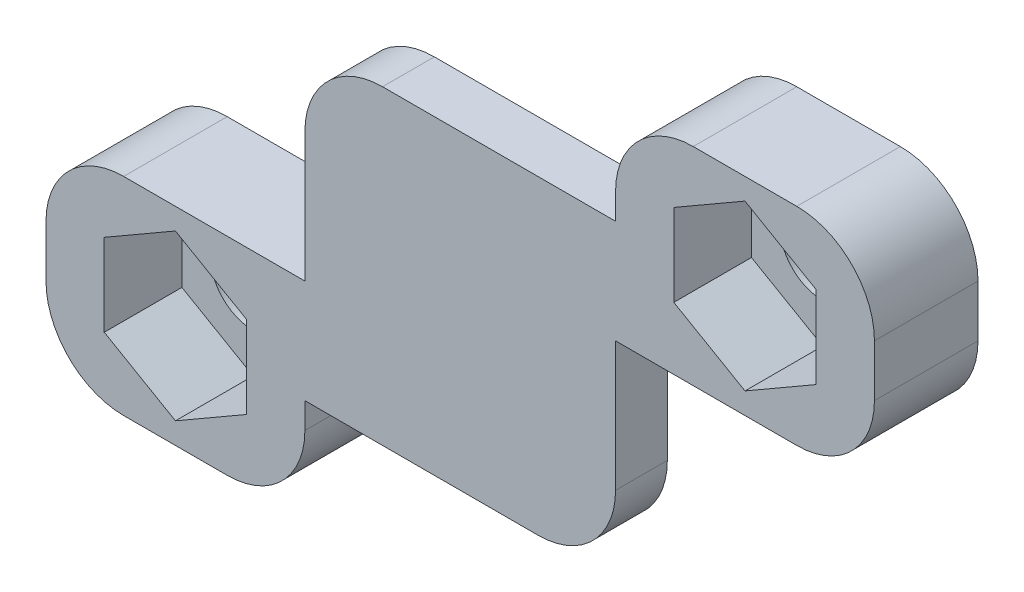
SolidWorks part; units mm, degrees
ref_plane "Front Plane" through (0, 0, 0) normal (0, 0, 1) x (1, 0, 0)
ref_plane "Top Plane" through (0, 0, 0) normal (0, 1, 0) x (1, 0, 0)
ref_plane "Right Plane" through (0, 0, 0) normal (1, 0, 0) x (0, 0, -1)
sketch "Sketch7" plane through (0, 0, 0) normal (0, 0, 1) x (1, 0, 0)
  line L1 (6, -6) -> (-6, -6)
  line L2 (6, -6) -> (6, 6)
  line L3 (6, 6) -> (-6, 6)
  line L4 (-6, -6) -> (-6, 6)
  line L5 (6, -6) -> (-6, 6) construction
  line L6 (6, 6) -> (-6, -6) construction
  line L7 (-6, -10) -> (-16, -10)
  line L8 (-6, -10) -> (-6, -2)
  line L9 (-6, -2) -> (-16, -2)
  line L10 (-16, -10) -> (-16, -2)
  line L11 (6, 10) -> (16, 10)
  line L12 (6, 10) -> (6, 2)
  line L13 (6, 2) -> (16, 2)
  line L14 (16, 10) -> (16, 2)
  circle A0 centre (-11, -6) radius 1.65
  circle A1 centre (11, 6) radius 1.65
  point P0 (0, 0)
  dimension "D9" = 3.3
  dimension "D10" = 3.3
  dimension "D11" = 4
  dimension "D12" = 5
  dimension "D13" = 4
  dimension "D14" = 5
  dimension "D1" = 12
  dimension "D2" = 12
  dimension "D3" = 8
  dimension "D4" = 8
  dimension "D5" = 4
  dimension "D6" = 4
  dimension "D7" = 10
  dimension "D8" = 10
extrude "Boss-Extrude2" add sketch "Sketch7" along normal blind 4 contours L10 L7 L4 L8 L9 A0 | L4 L1 L2 L3 | L14 L11 L2 L12 L13 A1
sketch "Sketch9" plane through (0, 0, 4) normal (0, 0, 1) x (1, 0, 0)
  line L1 (-11, -2.8246) -> (-13.75, -4.4123)
  line L2 (-13.75, -4.4123) -> (-13.75, -7.5877)
  line L3 (-13.75, -7.5877) -> (-11, -9.1754)
  line L4 (-11, -9.1754) -> (-8.25, -7.5877)
  line L5 (-8.25, -7.5877) -> (-8.25, -4.4123)
  line L6 (-8.25, -4.4123) -> (-11, -2.8246)
  line L7 (11, 2.8246) -> (13.75, 4.4123)
  line L8 (13.75, 4.4123) -> (13.75, 7.5877)
  line L9 (13.75, 7.5877) -> (11, 9.1754)
  line L10 (11, 9.1754) -> (8.25, 7.5877)
  line L11 (8.25, 7.5877) -> (8.25, 4.4123)
  line L12 (8.25, 4.4123) -> (11, 2.8246)
  circle A0 centre (-11, -6) radius 2.75 construction
  circle A1 centre (11, 6) radius 2.75 construction
  dimension "D1" = 5.5
  dimension "D2" = 5.5
extrude "Cut-Extrude6" cut sketch "Sketch9" against normal blind 3
fillet "Fillet3" radius 3 8 edges at (-16, -2, 2) (-6, 6, 2) (6, 10, 2) (16, 10, 2) (16, 2, 2) (6, -6, 2) (-6, -10, 2) (-16, -10, 2)
sketch "Sketch10" plane through (0, 0, 0) normal (0, 0, -1) x (-1, 0, 0)
  line L1 (6, -6) -> (-6, -6)
  line L2 (6, -6) -> (6, 6)
  line L3 (6, 6) -> (-6, 6)
  line L4 (-6, -6) -> (-6, 6)
  line L5 (6, -6) -> (-6, 6) construction
  line L6 (6, 6) -> (-6, -6) construction
  point P0 (0, 0)
extrude "Cut-Extrude7" cut sketch "Sketch10" against normal blind 2
